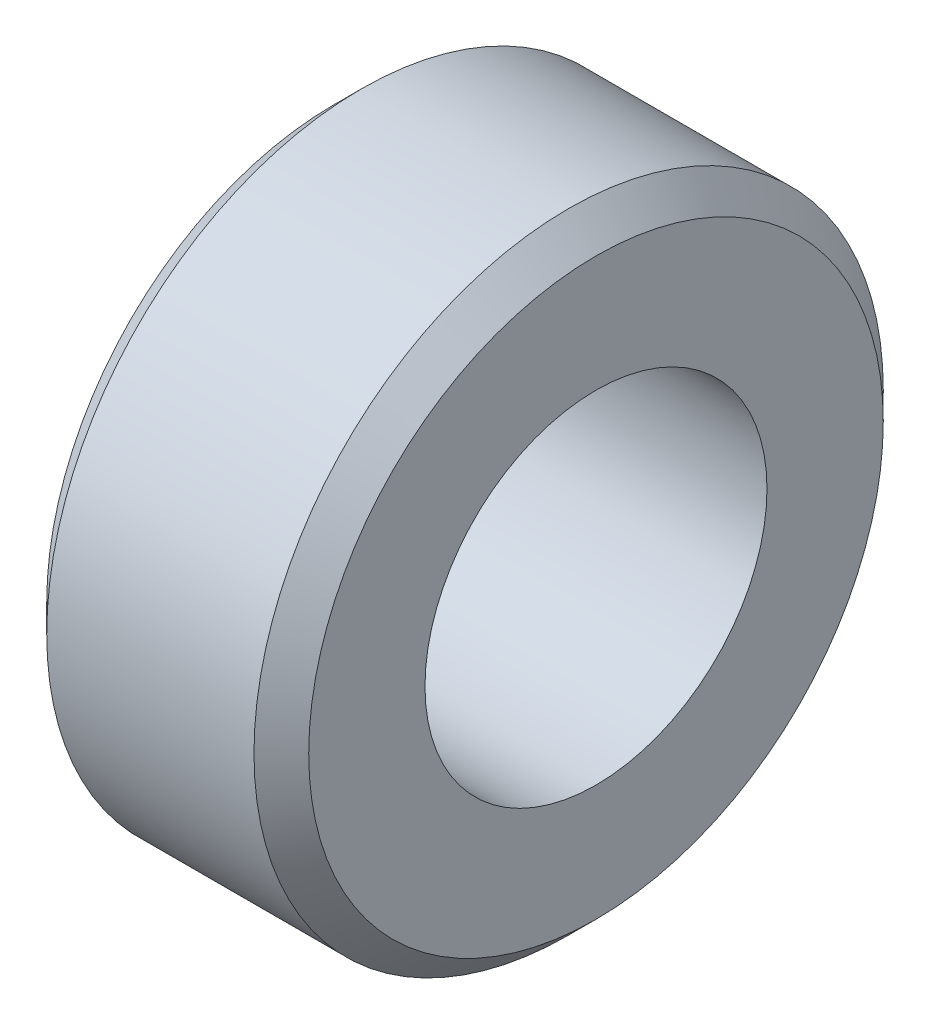
SolidWorks part; units mm, degrees
material "AISI 1020"
ref_plane "Plano frontal" through (0, 0, 0) normal (0, 0, 1) x (1, 0, 0)
ref_plane "Plano superior" through (0, 0, 0) normal (0, 1, 0) x (1, 0, 0)
ref_plane "Plano direito" through (0, 0, 0) normal (1, 0, 0) x (0, 0, -1)
sketch "Esboço1" plane through (0, 0, 0) normal (0, 0, 1) x (1, 0, 0)
  line L0 (-9.575, 0) -> (9.575, 0) construction
  line L1 (-9.575, 21) -> (-7.575, 23)
  line L2 (-9.575, 12.5) -> (9.575, 12.5)
  line L3 (-9.575, 12.5) -> (-9.575, 21)
  line L4 (-7.575, 23) -> (7.575, 23)
  line L5 (9.575, 12.5) -> (9.575, 21)
  line L6 (9.575, 21) -> (7.575, 23)
  point P4 (9.575, 23)
  point P5 (-9.575, 23)
  point P7 (0, 0)
  point P8 (0, 0)
  dimension "D1" = 25
  dimension "D2" = 46
  dimension "D3" = 19.15
revolve "Revolução1" add sketch "Esboço1" angle 360 about L0
